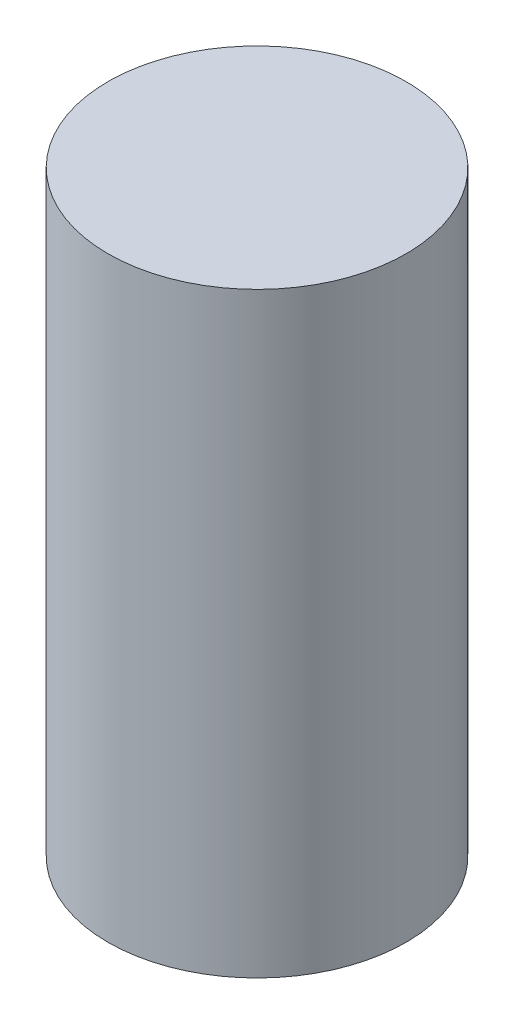
SolidWorks part; units mm, degrees
ref_plane "Front Plane" through (0, 0, 0) normal (0, 0, 1) x (1, 0, 0)
ref_plane "Top Plane" through (0, 0, 0) normal (0, 1, 0) x (1, 0, 0)
ref_plane "Right Plane" through (0, 0, 0) normal (1, 0, 0) x (0, 0, -1)
sketch "Sketch1" plane through (0, 0, 0) normal (0, 1, 0) x (1, 0, 0)
  circle A0 centre (0, 0) radius 41.275
  dimension "D1" = 82.55
extrude "Boss-Extrude1" add sketch "Sketch1" along normal blind 165.1
